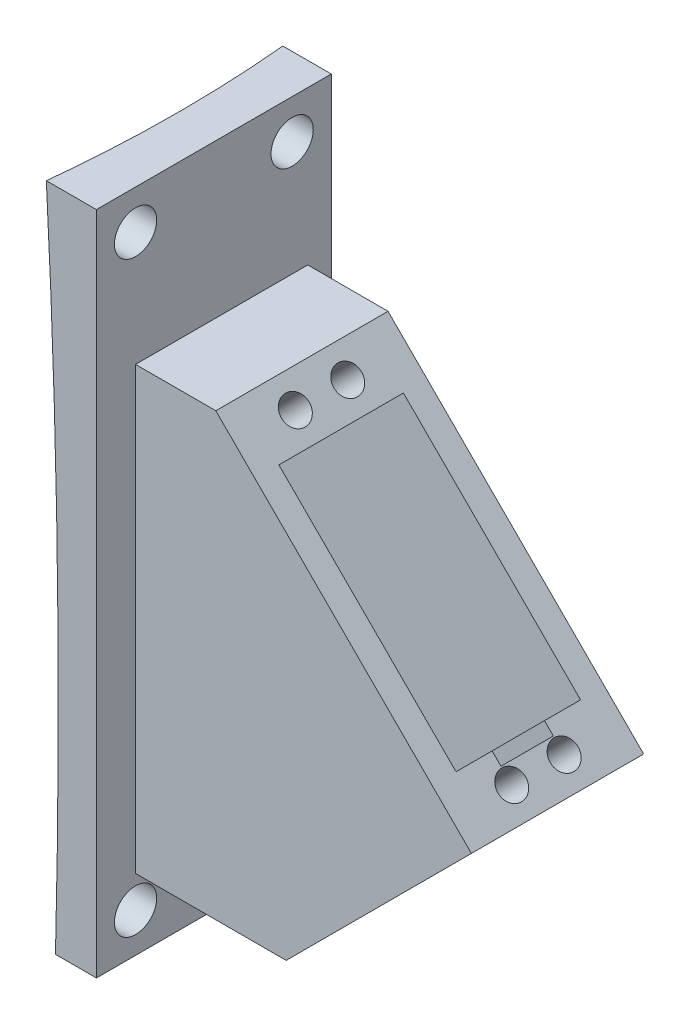
SolidWorks part; units mm, degrees
material "Nylon 101"
ref_plane "Front Plane" through (0, 0, 0) normal (0, 0, 1) x (1, 0, 0)
ref_plane "Top Plane" through (0, 0, 0) normal (0, 1, 0) x (1, 0, 0)
ref_plane "Right Plane" through (0, 0, 0) normal (1, 0, 0) x (0, 0, -1)
sketch "Sketch1" plane through (0, 0, 0) normal (1, 0, 0) x (0, 0, -1)
  line L1 (-7.62, -23.625) -> (7.62, -23.625)
  line L2 (-7.62, -23.625) -> (-7.62, 23.625)
  line L3 (-7.62, 23.625) -> (7.62, 23.625)
  line L4 (7.62, -23.625) -> (7.62, 23.625)
  line L5 (-7.62, -23.625) -> (7.62, 23.625) construction
  line L6 (-7.62, 23.625) -> (7.62, -23.625) construction
  point P0 (0, 0)
  dimension "D1" = 15.24
  dimension "D2" = 47.25
extrude "Boss-Extrude1" add sketch "Sketch1" along normal blind 29
sketch "Sketch8" plane through (0, 0, 0) normal (0, 1, 0) x (1, 0, 0)
  line L0 (8.89, -7.62) -> (8.89, 7.62) construction
  line L1 (29, -7.62) -> (0, -7.62) construction
  line L2 (29, 7.62) -> (0, 7.62) construction
  line L4 (0, -7.62) -> (0, 7.62) construction
  line L5 (8.89, 0) -> (-1363.98, 0) construction
  line L6 (-1363.98, 509.27) -> (-1363.98, -509.27)
  ellipse E0 centre (-1363.98, 0) end of major axis (8.89, 0) minor radius 509.27 (-1363.98, -509.27) -> (-1363.98, 509.27) ccw
  point P14 (-1363.98, 0)
  dimension "D1" = 8.89
  dimension "D2" = 1372.87
  dimension "D3" = 1018.54
revolve "Cut-Revolve1" cut sketch "Sketch8" angle 360 about L6
sketch "Sketch9" plane through (0, 0, 7.62) normal (0, 0, 1) x (1, 0, 0)
  line L0 (29, -23.625) -> (57.2937, -23.625)
  line L1 (57.2937, -23.625) -> (29, 23.625)
  line L2 (29, 23.625) -> (29, -23.625)
extrude "Boss-Extrude2" add sketch "Sketch9" against normal blind 15.24
ref_point "Point1"
sketch "Sketch11" plane through (0, 0, -7.62) normal (0, 0, -1) x (-1, 0, 0)
  line L0 (-8.533, 23.625) -> (-35.4738, 50.5658)
  line L1 (1364.0974, -1372.87) -> (-8.7726, 0) construction
  line L2 (-35.4738, 50.5658) -> (-71.0711, 14.9685)
  line L3 (-71.0711, 14.9685) -> (-48.5444, -9.0138)
  line L4 (-8.533, 23.625) -> (-28.8894, 23.625)
  line L5 (-28.8894, 23.625) -> (-48.5444, -9.0138)
  line L6 (-57.2937, -23.625) -> (-29, 23.625) construction
  dimension "D1" = 38.1
  dimension "D2" = 38.1
extrude "Boss-Extrude3" add sketch "Sketch11" against normal blind 27.94 from offset 6.35
sketch "Sketch12" plane through (43.0198, 43.0198, 0) normal (0.7071, 0.7071, 0) x (0, 0, -1)
  line L0 (13.97, 10.6717) -> (13.97, -39.6705) construction
  line L1 (-10.1003, 5.8206) -> (10.1003, 5.8206)
  line L2 (-10.1003, 5.8206) -> (-10.1003, -34.8194)
  line L3 (-10.1003, -34.8194) -> (10.1003, -34.8194)
  line L4 (10.1003, 5.8206) -> (10.1003, -34.8194)
  line L5 (-10.1003, 5.8206) -> (10.1003, -34.8194) construction
  line L6 (-10.1003, -34.8194) -> (10.1003, 5.8206) construction
  line L7 (-13.97, 10.6717) -> (13.97, 10.6717) construction
  point P0 (0, -14.4994)
  point P6 (10.1003, -14.4994)
  point P9 (13.97, -14.4994)
  point P10 (0, 5.8206)
  point P13 (0, 10.6717)
  dimension "D1" = 40.64
  dimension "D2" = 20.2006
sketch "Sketch13" plane through (0, 0, -7.62) normal (0, 0, -1) x (-1, 0, 0)
  line L0 (-61.6723, 5.5697) -> (-8.533, -23.625)
  line L1 (-8.533, -23.625) -> (-25.0252, -53.6437)
  line L2 (-25.0252, -53.6437) -> (-79.4171, -23.7609)
  line L3 (-79.4171, -23.7609) -> (-61.6723, 5.5697)
extrude "Cut-Extrude4" cut sketch "Sketch13" against normal through all both and the other way through all
sketch "Sketch15" plane through (0, 0, 7.62) normal (0, 0, 1) x (1, 0, 0)
  line L0 (8.533, -23.625) -> (45.2091, -3.4752) construction
  line L1 (13.867, 72.765) -> (1.133, 72.765)
  line L2 (13.867, 72.765) -> (13.867, -35.185)
  line L3 (13.867, -35.185) -> (1.133, -35.185)
  line L4 (1.133, 72.765) -> (1.133, -35.185)
  dimension "D1" = 12.7
  dimension "D2" = 107.95
  dimension "D3" = 5.334
extrude "Boss-Extrude4" add sketch "Sketch15" against normal blind 38.1 from offset 12.7
sketch "Sketch16" plane through (0, 0, 0) normal (0, 1, 0) x (1, 0, 0)
  line L0 (8.771, -44.3468) -> (8.771, 44.3468) construction
  line L1 (8.771, 0) -> (-1364.099, 0) construction
  line L2 (-1364.099, 509.27) -> (-1364.099, -509.27)
  ellipse E0 centre (-1364.099, 0) end of major axis (8.771, 0) minor radius 509.27 (-1364.099, -509.27) -> (-1364.099, 509.27) ccw
  point P6 (-1364.099, 0)
  dimension "D1" = 1372.87
  dimension "D2" = 1018.54
  dimension "D3" = 88.6936
revolve "Cut-Revolve2" cut sketch "Sketch16" angle 360 about L2
sketch "Sketch17" plane through (13.867, 0, 0) normal (1, 0, 0) x (0, 0, -1)
  line L0 (-20.32, -35.185) -> (-20.32, 72.765) construction
  line L1 (17.78, -35.185) -> (-20.32, -35.185) construction
  line L2 (17.78, -35.185) -> (17.78, 72.765) construction
  line L3 (17.78, 72.765) -> (-20.32, 72.765) construction
  circle A0 centre (-13.97, -28.835) radius 3.429
  circle A1 centre (-13.97, 66.415) radius 3.429
  circle A2 centre (11.43, 66.415) radius 3.429
  circle A3 centre (11.43, -28.835) radius 3.429
  dimension "D1" = 6.858
  dimension "D3" = 6.35
  dimension "D6" = 6.35
  dimension "D7" = 6.35
  dimension "D2" = 6.35
  dimension "D4" = 2
  dimension "D5" = 2
extrude "Cut-Extrude6" cut sketch "Sketch17" against normal through all
sketch "Sketch19" plane through (0, 0, 7.62) normal (0, 0, 1) x (1, 0, 0)
  line L4 (28.8894, 23.625) -> (13.867, 23.625)
  line L5 (13.867, 23.625) -> (13.867, -20.6945)
  line L6 (13.867, -20.6945) -> (45.2091, -3.4752)
  line L9 (13.867, 23.625) -> (13.867, -20.6945)
  line L10 (13.867, -20.6945) -> (45.2091, -3.4752)
  line L12 (28.8894, 23.625) -> (13.867, 23.625)
  line L14 (45.2091, -3.4752) -> (28.8894, 23.625)
  line L15 (45.2091, -3.4752) -> (28.8894, 23.625)
  dimension "D1" = 0
extrude "Boss-Extrude9" add sketch "Sketch19" along normal up to surface (6.35 mm away) up to face at (41.4932, 18.6297, 13.97)
sketch "Sketch20" plane through (0, 0, -7.62) normal (0, 0, -1) x (-1, 0, 0)
  line L4 (-45.2091, -3.4752) -> (-13.867, -20.6945)
  line L5 (-13.867, -20.6945) -> (-13.867, 23.625)
  line L6 (-13.867, 23.625) -> (-28.8894, 23.625)
  line L8 (-45.2091, -3.4752) -> (-13.867, -20.6945)
  line L9 (-13.867, -20.6945) -> (-13.867, 23.625)
  line L12 (-13.867, 23.625) -> (-28.8894, 23.625)
  line L14 (-28.8894, 23.625) -> (-45.2091, -3.4752)
  line L15 (-28.8894, 23.625) -> (-45.2091, -3.4752)
  dimension "D1" = 0
extrude "Boss-Extrude10" add sketch "Sketch20" along normal up to surface (6.35 mm away) up to face at (41.4932, 18.6297, -13.97)
extrude "Cut-Extrude8" cut sketch "Sketch12" against normal blind 38.1
sketch "Sketch21" plane through (43.0198, 43.0198, 0) normal (0.7071, 0.7071, 0) x (0, 0, -1)
  line L1 (-13.97, -39.6705) -> (13.97, -39.6705)
  line L2 (-13.97, -39.6705) -> (-13.97, 10.6717)
  line L3 (-13.97, 10.6717) -> (13.97, 10.6717)
  line L4 (13.97, -39.6705) -> (13.97, 10.6717)
extrude "Cut-Extrude9" cut sketch "Sketch21" against normal blind 8 contours L1 L4 L3 L2
sketch "Sketch22" plane through (28.0513, -28.0513, 0) normal (-0.7071, 0.7071, 0) x (0, 0, 1)
  line L1 (13.97, 60.8391) -> (-13.97, 60.8391)
  line L2 (13.97, 60.8391) -> (13.97, 52.8391)
  line L3 (13.97, 52.8391) -> (-13.97, 52.8391)
  line L4 (-13.97, 60.8391) -> (-13.97, 52.8391)
extrude "Cut-Extrude10" cut sketch "Sketch22" against normal blind 2.54
sketch "Sketch23" plane through (0, 0, 0) normal (0, 0, 1) x (1, 0, 0)
  line L0 (29.8169, 44.9089) -> (26.8832, 47.8426)
  line L1 (26.8832, 47.8426) -> (13.867, 47.8426)
  line L2 (13.867, -35.185) -> (13.867, 72.765) construction
  line L3 (13.867, 47.8426) -> (13.867, 28.959)
  line L4 (13.867, 28.959) -> (29.8169, 44.9089)
  line L5 (65.5913, 9.1346) -> (13.867, -20.6945)
  line L6 (13.867, -20.6945) -> (13.867, -23.6743)
  line L8 (68.3479, 6.3779) -> (65.5913, 9.1346)
  line L9 (68.3479, 6.3779) -> (61.984, 12.7419) construction
  line L10 (26.8832, 47.8426) -> (33.2472, 41.4787) construction
  line L12 (68.3479, 6.3779) -> (38.2958, -23.6743)
  line L13 (38.2958, -23.6743) -> (13.867, -23.6743)
  dimension "D1" = 9
  dimension "D2" = 9
extrude "Boss-Extrude11" add sketch "Sketch23" along normal mid plane 27.94
sketch "Sketch24" plane through (12.4167, -21.5309, 0) normal (-0.4996, 0.8663, 0) x (0.8663, 0.4996, 0)
  line L4 (41.7088, -10.1003) -> (41.7088, 10.1003)
  line L5 (41.7088, 10.1003) -> (30.2173, 10.1003)
  line L6 (30.2173, 10.1003) -> (30.2173, -10.1003)
  line L7 (30.2173, -10.1003) -> (41.7088, -10.1003)
  line L8 (41.7088, -10.1003) -> (41.7088, 10.1003)
  line L9 (41.7088, 10.1003) -> (30.2173, 10.1003)
  line L10 (30.2173, 10.1003) -> (30.2173, -10.1003)
  line L11 (30.2173, -10.1003) -> (41.7088, -10.1003)
  dimension "D1" = 0
extrude "Cut-Extrude11" cut sketch "Sketch24" against normal through all
sketch "Sketch25" plane through (37.3629, 37.3629, 0) normal (0.7071, 0.7071, 0) x (0, 0, -1)
  line L0 (-4.25, 10.3206) -> (4.25, 10.3206) construction
  line L1 (0, 14.8206) -> (0, 5.8206) construction
  line L2 (-13.97, 14.8206) -> (13.97, 14.8206) construction
  line L3 (10.1003, 5.8206) -> (-10.1003, 5.8206) construction
  line L4 (-4.25, -39.3194) -> (4.25, -39.3194) construction
  line L5 (0, -34.8194) -> (0, -43.8194) construction
  line L6 (-10.1003, -34.8194) -> (10.1003, -34.8194) construction
  line L9 (-13.97, -43.8194) -> (13.97, -43.8194) construction
  circle A0 centre (-4.25, 10.3206) radius 2.25
  circle A1 centre (4.25, 10.3206) radius 2.25
  circle A2 centre (-4.25, -39.3194) radius 2.25
  circle A3 centre (4.25, -39.3194) radius 2.25
  point P4 (0, 10.3206)
  point P12 (0, 10.3206)
  point P17 (0, -39.3194)
  point P20 (0, -39.3194)
  point P31 (0, -43.8194)
  dimension "D1" = 4.5
  dimension "D2" = 8.5
extrude "Cut-Extrude12" cut sketch "Sketch25" against normal blind 18
sketch "Sketch26" plane through (37.3629, 37.3629, 0) normal (0.7071, 0.7071, 0) x (0, 0, -1)
  line L0 (-10.1003, -34.8194) -> (10.1003, -34.8194) construction
  line L2 (4.25, -34.8194) -> (4.25, -36.8514)
  line L3 (4.25, -36.8514) -> (-4.25, -36.8514)
  line L4 (-4.25, -34.8194) -> (-4.25, -36.8514)
  line L7 (-4.25, -34.8194) -> (4.25, -34.8194)
  point P0 (0, -34.8194)
  point P2 (0, 0)
extrude "Cut-Extrude13" cut sketch "Sketch26" against normal up to surface (30.9 mm away)
